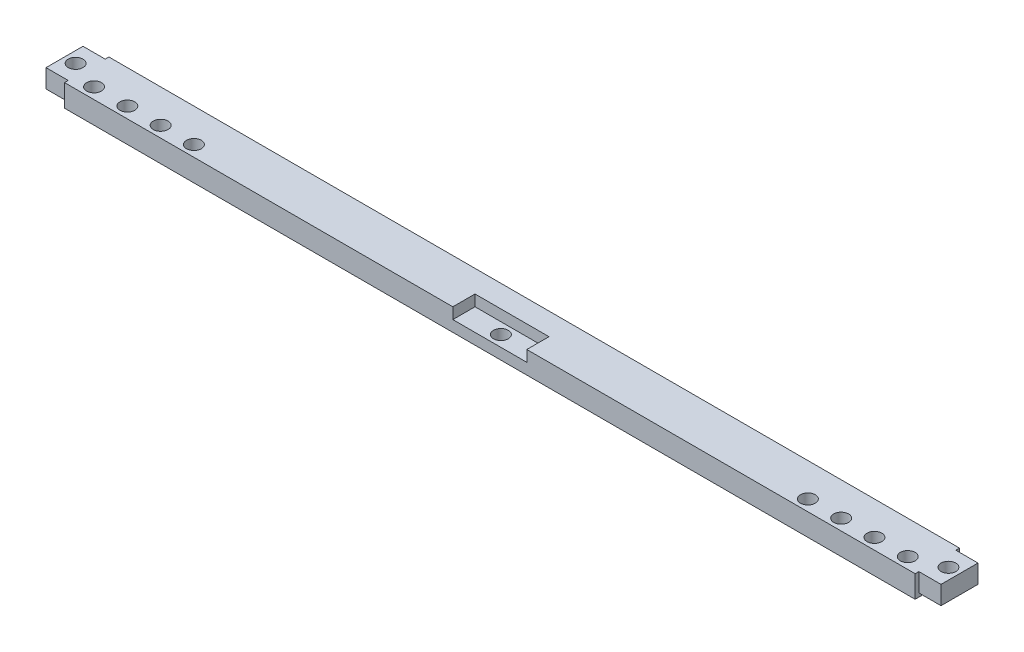
SolidWorks part; units mm, degrees
ref_plane "Front Plane" through (0, 0, 0) normal (0, 0, 1) x (1, 0, 0)
ref_plane "Top Plane" through (0, 0, 0) normal (0, 1, 0) x (1, 0, 0)
ref_plane "Right Plane" through (0, 0, 0) normal (1, 0, 0) x (0, 0, -1)
sketch "Sketch1" plane through (0, 0, 0) normal (0, 1, 0) x (1, 0, 0)
  line L1 (-307.34, -15.24) -> (307.34, -15.24)
  line L2 (-307.34, -15.24) -> (-307.34, 15.24)
  line L3 (-307.34, 15.24) -> (307.34, 15.24)
  line L4 (307.34, -15.24) -> (307.34, 15.24)
  line L5 (-307.34, -15.24) -> (307.34, 15.24) construction
  line L6 (-307.34, 15.24) -> (307.34, -15.24) construction
  point P0 (0, 0)
  point P6 (0, 0)
extrude "Boss-Extrude1" add sketch "Sketch1" along normal blind 15.24
sketch "Sketch2" plane through (0, 15.24, 0) normal (0, 1, 0) x (1, 0, 0)
  line L1 (-307.34, 15.24) -> (-292.1, 15.24)
  line L2 (-307.34, 15.24) -> (-307.34, 12.7)
  line L3 (-307.34, 12.7) -> (-292.1, 12.7)
  line L4 (-292.1, 15.24) -> (-292.1, 12.7)
  line L5 (-307.34, -15.24) -> (-292.1, -15.24)
  line L6 (-307.34, -15.24) -> (-307.34, -12.7)
  line L7 (-307.34, -12.7) -> (-292.1, -12.7)
  line L8 (-292.1, -15.24) -> (-292.1, -12.7)
  line L9 (307.34, 15.24) -> (292.1, 15.24)
  line L10 (307.34, 15.24) -> (307.34, 12.7)
  line L11 (307.34, 12.7) -> (292.1, 12.7)
  line L12 (292.1, 15.24) -> (292.1, 12.7)
  line L13 (307.34, -15.24) -> (292.1, -15.24)
  line L14 (307.34, -15.24) -> (307.34, -12.7)
  line L15 (307.34, -12.7) -> (292.1, -12.7)
  line L16 (292.1, -15.24) -> (292.1, -12.7)
extrude "Cut-Extrude1" cut sketch "Sketch2" against normal blind 15.24
sketch "Sketch3" plane through (0, 0, 0) normal (0, -1, 0) x (1, 0, 0)
  line L1 (307.34, -12.7) -> (292.1, -12.7)
  line L2 (307.34, -12.7) -> (307.34, 12.7)
  line L3 (307.34, 12.7) -> (292.1, 12.7)
  line L4 (292.1, -12.7) -> (292.1, 12.7)
  line L5 (-307.34, -12.7) -> (-292.1, -12.7)
  line L6 (-307.34, -12.7) -> (-307.34, 12.7)
  line L7 (-307.34, 12.7) -> (-292.1, 12.7)
  line L8 (-292.1, -12.7) -> (-292.1, 12.7)
extrude "Cut-Extrude2" cut sketch "Sketch3" against normal blind 2.54
sketch "Sketch4" plane through (0, 15.24, 0) normal (0, 1, 0) x (1, 0, 0)
  circle A0 centre (-299.72, 0) radius 5.08
  circle A1 centre (299.72, 0) radius 5.08
extrude "Cut-Extrude3" cut sketch "Sketch4" against normal blind 17.78
sketch "Sketch5" plane through (0, 15.24, 0) normal (0, 1, 0) x (1, 0, 0)
  line L1 (-25.4, -15.24) -> (25.4, -15.24)
  line L2 (-25.4, -15.24) -> (-25.4, 0)
  line L3 (-25.4, 0) -> (25.4, 0)
  line L4 (25.4, -15.24) -> (25.4, 0)
  line L5 (-25.4, -15.24) -> (25.4, 0) construction
  line L6 (-25.4, 0) -> (25.4, -15.24) construction
  point P0 (0, -7.62)
  point P5 (0, 0)
extrude "Cut-Extrude4" cut sketch "Sketch5" against normal blind 7.62
sketch "Sketch6" plane through (0, 7.62, 0) normal (0, 1, 0) x (1, 0, 0)
  circle A0 centre (0, -7.62) radius 5.08
extrude "Cut-Extrude5" cut sketch "Sketch6" against normal blind 12.7
sketch "Sketch7" plane through (0, 15.24, 0) normal (0, 1, 0) x (1, 0, 0)
  circle A0 centre (-279.4, -7.62) radius 5.08
  circle A1 centre (-256.54, -7.62) radius 5.08
  circle A2 centre (-233.68, -7.62) radius 5.08
  circle A3 centre (-210.82, -7.62) radius 5.08
  circle A4 centre (279.4, -7.62) radius 5.08
  circle A5 centre (256.54, -7.62) radius 5.08
  circle A6 centre (233.68, -7.62) radius 5.08
  circle A7 centre (210.82, -7.62) radius 5.08
extrude "Cut-Extrude6" cut sketch "Sketch7" against normal blind 17.78
